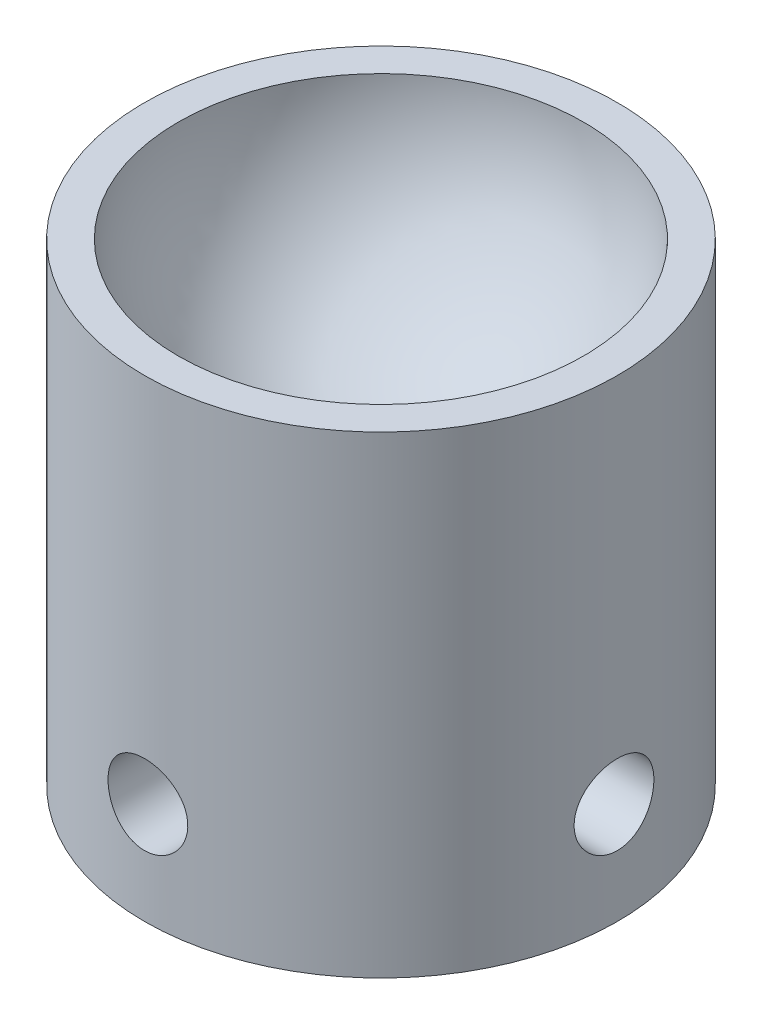
SolidWorks part; units mm, degrees
ref_plane "Front Plane" through (0, 0, 0) normal (0, 0, 1) x (1, 0, 0)
ref_plane "Top Plane" through (0, 0, 0) normal (0, 1, 0) x (1, 0, 0)
ref_plane "Right Plane" through (0, 0, 0) normal (1, 0, 0) x (0, 0, -1)
sketch "Sketch1" plane through (0, 0, 0) normal (0, 1, 0) x (1, 0, 0)
  circle A0 centre (0, 0) radius 8.89
  dimension "D1" = 17.78
extrude "Boss-Extrude1" add sketch "Sketch1" along normal blind 17.78
sketch "Sketch2" plane through (0, 0, 0) normal (0, 0, 1) x (1, 0, 0)
  line L0 (8.89, 17.78) -> (-8.89, 17.78) construction
  line L1 (0, 10.16) -> (0, 25.4)
  arc A0 (0, 25.4) -> (0, 10.16) centre (0, 17.78) ccw
  dimension "D1" = 15.24
revolve "Cut-Revolve1" cut sketch "Sketch2" angle 360 about L1
sketch "Sketch3" plane through (0, 0, 0) normal (0, 0, 1) x (1, 0, 0)
  circle A0 centre (0, 3.81) radius 1.5
  dimension "D1" = 3
  dimension "D2" = 3.81
extrude "Cut-Extrude1" cut sketch "Sketch3" along normal through all both and the other way through all
pattern_circular "CirPattern1" count 2 over 90 about axis through (0, 0, 0) along (0, 1, 0) of "Cut-Extrude1"
